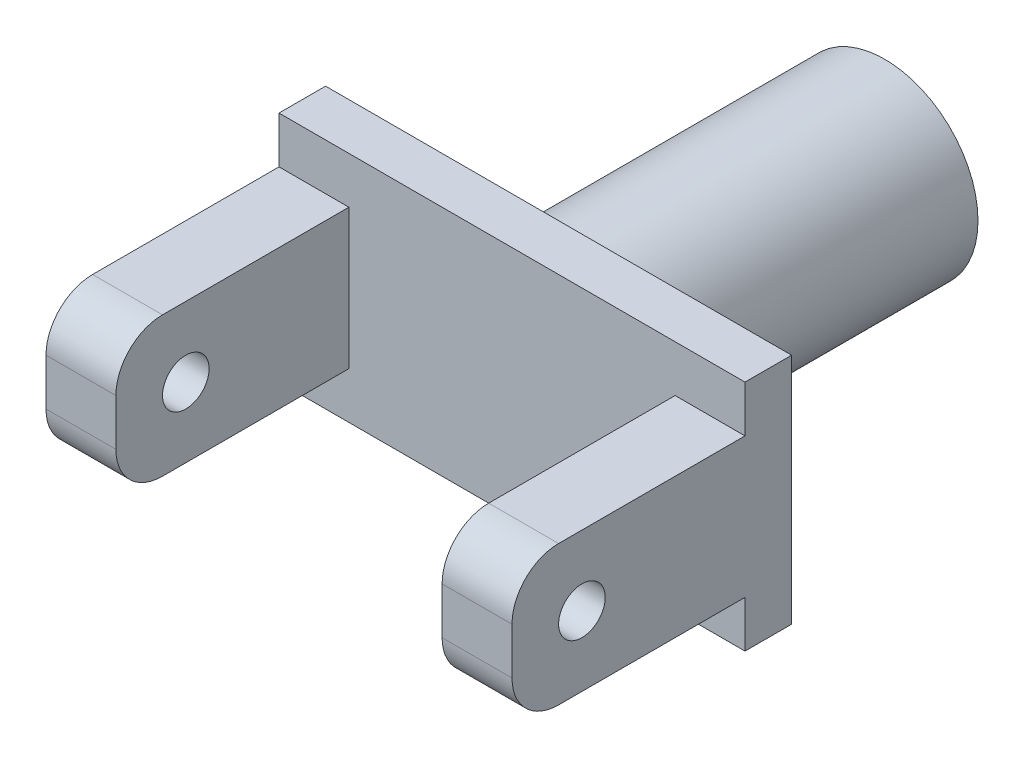
SolidWorks part; units mm, degrees
ref_plane "Спереди" through (0, 0, 0) normal (0, 0, 1) x (1, 0, 0)
ref_plane "Сверху" through (0, 0, 0) normal (0, 1, 0) x (1, 0, 0)
ref_plane "Справа" through (0, 0, 0) normal (1, 0, 0) x (0, 0, -1)
sketch "Эскиз1" plane through (0, 0, 0) normal (0, 0, 1) x (1, 0, 0)
  circle A0 centre (0, 0) radius 15
  circle A1 centre (0, 0) radius 20
  dimension "D1" = 30
  dimension "D2" = 5
extrude "Бобышка-Вытянуть1" add sketch "Эскиз1" along normal blind 70
sketch "Эскиз2" plane through (0, 0, 70) normal (0, 0, 1) x (1, 0, 0)
  line L1 (-50, -25) -> (50, -25)
  line L2 (-50, -25) -> (-50, 25)
  line L3 (-50, 25) -> (50, 25)
  line L4 (50, -25) -> (50, 25)
  line L5 (-50, -25) -> (50, 25) construction
  line L6 (-50, 25) -> (50, -25) construction
  point P0 (0, 0)
  dimension "D1" = 100
  dimension "D2" = 50
extrude "Бобышка-Вытянуть2" add sketch "Эскиз2" along normal blind 10
sketch "Эскиз3" plane through (0, 0, 80) normal (0, 0, 1) x (1, 0, 0)
  line L0 (-50, 0) -> (50, 0) construction
  line L1 (-50, 25) -> (-50, -25) construction
  line L2 (50, -25) -> (50, 25) construction
  line L3 (0, 25) -> (0, -25) construction
  line L4 (50, 25) -> (-50, 25) construction
  line L5 (-50, -25) -> (50, -25) construction
  line L7 (-50, -15) -> (-35, -15)
  line L8 (-50, -15) -> (-50, 15)
  line L9 (-50, 15) -> (-35, 15)
  line L10 (-35, -15) -> (-35, 15)
  point P12 (-50, 0)
  dimension "D1" = 30
  dimension "D2" = 15
extrude "Бобышка-Вытянуть3" add sketch "Эскиз3" along normal blind 50
fillet "Скругление1" radius 10 2 edges at (-42.5, 15, 130) (-42.5, -15, 130)
sketch "Эскиз4" plane through (-50, 0, 0) normal (-1, 0, 0) x (0, 0, 1)
  line L0 (0, 0) -> (115, 0) construction
  line L1 (0, 20) -> (0, -20) construction
  circle A0 centre (115, 0) radius 5
  point P5 (115, 0)
  dimension "D2" = 10
  dimension "D1" = 115
extrude "Вырез-Вытянуть1" cut sketch "Эскиз4" against normal blind 50
ref_plane "Плоскость1" through (0, 0, 0) normal (1, 0, 0) x (0, 0, -1)
mirror "Зеркальное отражение2" about plane through (0, 0, 0) normal (1, 0, 0) of "Бобышка-Вытянуть3", "Скругление1", "Вырез-Вытянуть1"
